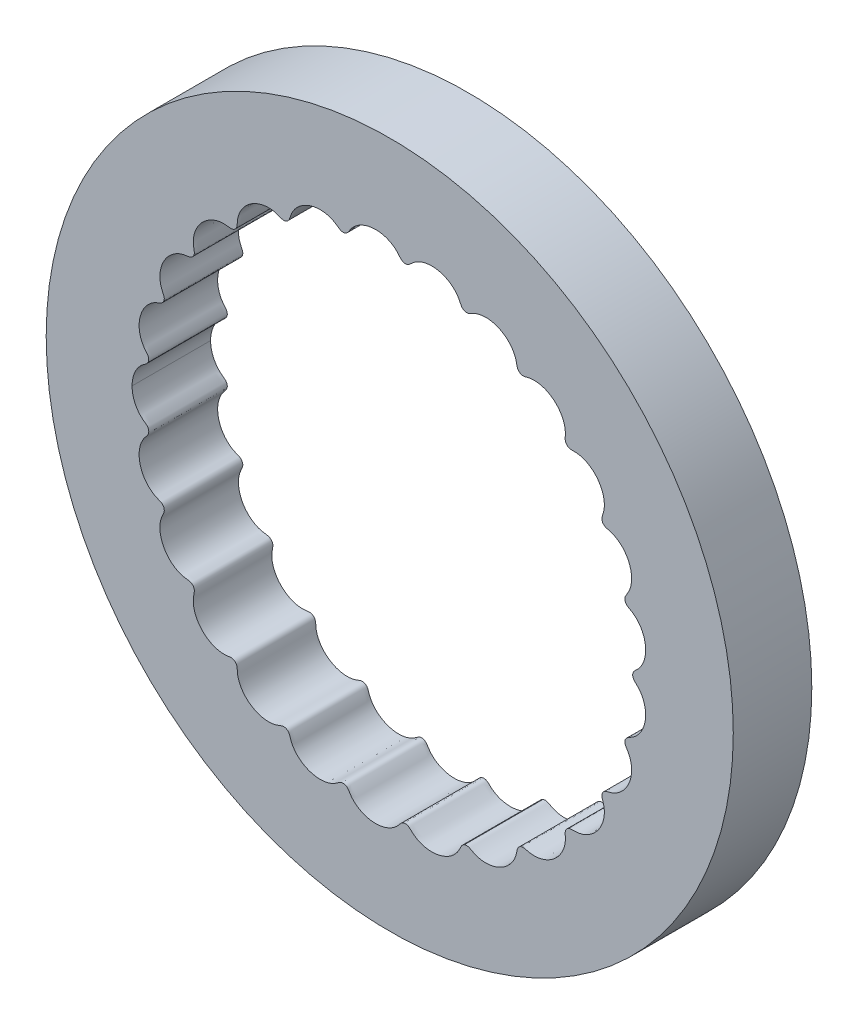
SolidWorks part; units mm, degrees
ref_plane "Plan de face" through (0, 0, 0) normal (0, 0, 1) x (1, 0, 0)
ref_plane "Plan de dessus" through (0, 0, 0) normal (0, 1, 0) x (1, 0, 0)
ref_plane "Plan de droite" through (0, 0, 0) normal (1, 0, 0) x (0, 0, -1)
sketch "Esquisse1" plane through (0, 0, 0) normal (0, 0, 1) x (1, 0, 0)
  line L0 (-1000, 0) -> (49000, 0) construction
  circle A1 centre (0, 0) radius 35
  spline S0 degree 4 poles (24.1426, 6.7991) (24.1177, 6.7609) (24.0692, 6.6836) (24.0004, 6.5645) (23.9483, 6.387) (23.9505, 6.1855) (24.0272, 5.9803) (24.1778, 5.8151) (24.3705, 5.7045) (24.5983, 5.5844) (24.8479, 5.4264) (25.1139, 5.2067) (25.3819, 4.9129) (25.6102, 4.583) (25.7961, 4.2235) (25.9371, 3.8403) (26.0305, 3.4429) (26.0756, 3.0373) (26.0716, 2.6291) (26.0179, 2.2244) (25.9151, 1.834) (25.7643, 1.4641) (25.5917, 1.1641) (25.4167, 0.9296) (25.2526, 0.7496) (25.1124, 0.6144) (24.9828, 0.4987) (24.8797, 0.3844) (24.8179, 0.2829) (24.7848, 0.2051) (24.7673, 0.1461) (24.7588, 0.1043) (24.7529, 0.0597) (24.7496, 0.0145) (24.7496, -0.0147) (24.7529, -0.06) (24.7589, -0.1048) (24.7675, -0.1468) (24.7852, -0.2061) (24.8185, -0.2842) (24.8808, -0.3859) (24.9847, -0.5005) (25.1148, -0.6166) (25.2554, -0.7525) (25.4198, -0.9333) (25.595, -1.1691) (25.7689, -1.4729) (25.9207, -1.8497) (26.0235, -2.2499) (26.0747, -2.6669) (26.0733, -3.0863) (26.0204, -3.5015) (25.917, -3.9063) (25.7644, -4.2943) (25.5662, -4.6548) (25.3259, -4.9815) (25.0816, -5.2331) (24.8519, -5.4186) (24.6671, -5.5402) (24.5395, -5.6139) (24.4102, -5.6846) (24.274, -5.758) (24.12, -5.8678) (23.9899, -6.0503) (23.9364, -6.2751) (23.9692, -6.4958) (24.0654, -6.6843) (24.1784, -6.8519) (24.2801, -7.019) (24.3936, -7.2353) (24.5034, -7.5077) (24.5951, -7.8454) (24.647, -8.2482) (24.6457, -8.6612) (24.576, -9.1855) (24.4176, -9.6961) (24.1747, -10.1766) (23.852, -10.6101) (23.5588, -10.9098) (23.241, -11.1578) (22.9466, -11.3291) (22.6921, -11.4408) (22.4727, -11.5135) (22.2939, -11.5615) (22.1013, -11.606) (21.9021, -11.6816) (21.7285, -11.8281) (21.6209, -12.0388) (21.6016, -12.2637) (21.6505, -12.4693) (21.7183, -12.6598) (21.7746, -12.8471) (21.8297, -13.085) (21.8672, -13.3762) (21.8707, -13.726) (21.8195, -14.1287) (21.7142, -14.528) (21.5148, -15.0178) (21.2331, -15.4721) (20.8771, -15.876) (20.4557, -16.2144) (20.0964, -16.4307) (19.7262, -16.5906) (19.3981, -16.6821) (19.1236, -16.7259) (18.8929, -16.7409) (18.7078, -16.7424) (18.5101, -16.7378) (18.2984, -16.7644) (18.0955, -16.8669) (17.9421, -17.0472) (17.8714, -17.2614) (17.8702, -17.4725) (17.8883, -17.6738) (17.8957, -17.8692) (17.8889, -18.1133) (17.8517, -18.4044) (17.7668, -18.7438) (17.6158, -19.1205) (17.4134, -19.4803) (17.1623, -19.8168) (16.8685, -20.1221) (16.5358, -20.3908) (16.1684, -20.6173) (15.771, -20.7957) (15.3688, -20.9145) (14.9702, -20.976) (14.6296, -20.9817) (14.3529, -20.9549) (14.1259, -20.9112) (13.9464, -20.866) (13.7558, -20.8128) (13.5435, -20.7889) (13.3222, -20.8417) (13.1314, -20.9817) (13.013, -21.1736) (12.9618, -21.3782) (12.9291, -21.5776) (12.887, -21.7685) (12.8188, -22.0029) (12.7093, -22.2752) (12.5416, -22.5821) (12.3006, -22.9086) (12.0142, -23.2057) (11.6866, -23.4682) (11.3255, -23.6897) (10.9359, -23.8661) (10.5233, -23.9928) (10.0937, -24.0655) (9.6744, -24.0792) (9.2731, -24.0382) (8.942, -23.9578) (8.6811, -23.862) (8.4724, -23.7624) (8.31, -23.6735) (8.1383, -23.575) (7.9372, -23.5018) (7.7049, -23.5021) (7.4781, -23.6007) (7.3169, -23.7729) (7.2208, -23.9706) (7.1156, -24.2034) (6.9743, -24.4604) (6.773, -24.7375) (6.4979, -25.0224) (6.1834, -25.2709) (5.8357, -25.4797) (5.4603, -25.6452) (5.0615, -25.7656) (4.6447, -25.8371) (4.2157, -25.8559) (3.7816, -25.8181) (3.3723, -25.7258) (2.9942, -25.5849) (2.6941, -25.4236) (2.4656, -25.2649) (2.2891, -25.1158) (2.1537, -24.9891) (2.0123, -24.8511) (1.8324, -24.7331) (1.553, -24.6659) (1.2621, -24.7546) (1.0754, -24.9576) (0.8891, -25.1941) (0.6967, -25.4018) (0.4476, -25.6153) (0.1257, -25.8218) (-0.2246, -25.9871) (-0.599, -26.1091) (-0.9909, -26.1853) (-1.3919, -26.2146) (-1.7962, -26.1958) (-2.1981, -26.1285) (-2.5915, -26.0119) (-2.9628, -25.849) (-3.3062, -25.6424) (-3.6154, -25.3948) (-3.8503, -25.1456) (-4.0231, -24.9087) (-4.157, -24.6911) (-4.2763, -24.5066) (-4.4563, -24.3545) (-4.6931, -24.2829) (-4.9238, -24.3097) (-5.115, -24.4061) (-5.2732, -24.5252) (-5.423, -24.6339) (-5.6174, -24.7592) (-5.864, -24.8876) (-6.1822, -25.0094) (-6.5751, -25.1011) (-6.9928, -25.1407) (-7.4281, -25.1231) (-7.8512, -25.0501) (-8.2556, -24.9263) (-8.636, -24.7563) (-8.9874, -24.5444) (-9.3058, -24.2932) (-9.5861, -24.0067) (-9.8229, -23.6892) (-9.9872, -23.3887) (-10.0948, -23.1158) (-10.1696, -22.8715) (-10.2411, -22.6635) (-10.3812, -22.4737) (-10.595, -22.3493) (-10.8256, -22.322) (-11.0338, -22.3709) (-11.2164, -22.4474) (-11.3887, -22.5149) (-11.6084, -22.5872) (-11.8793, -22.649) (-12.2179, -22.6866) (-12.6212, -22.6763) (-13.0353, -22.6095) (-13.4521, -22.4829) (-13.8453, -22.3049) (-14.2094, -22.0805) (-14.5395, -21.815) (-14.8313, -21.5131) (-15.0777, -21.1819) (-15.2753, -20.8275) (-15.4026, -20.5017) (-15.4765, -20.2177) (-15.5143, -19.9765) (-15.5318, -19.7817) (-15.5392, -19.5798) (-15.5656, -19.3704) (-15.6608, -19.166) (-15.8341, -19.0047) (-16.0476, -18.9266) (-16.2611, -18.9252) (-16.4568, -18.9543) (-16.6405, -18.9763) (-16.8713, -18.9908) (-17.1491, -18.9822) (-17.4862, -18.9332) (-17.8737, -18.8216) (-18.2576, -18.6527) (-18.6291, -18.4253) (-18.9648, -18.1541) (-19.2607, -17.8454) (-19.5135, -17.5053) (-19.7199, -17.1396) (-19.875, -16.7569) (-19.9769, -16.364) (-20.018, -16.0166) (-20.0178, -15.7231) (-19.9934, -15.4801) (-19.9613, -15.2872) (-19.9181, -15.0898) (-19.894, -14.8799) (-19.9394, -14.6589) (-20.0707, -14.462) (-20.2602, -14.3367) (-20.4672, -14.2852) (-20.6639, -14.2651) (-20.8473, -14.2402) (-21.0742, -14.196) (-21.3408, -14.1175) (-21.6546, -13.985) (-22.0015, -13.7794) (-22.3304, -13.5193) (-22.7055, -13.1302) (-23.0074, -12.6844) (-23.2291, -12.1981) (-23.3648, -11.6869) (-23.4186, -11.2774) (-23.4182, -10.8714) (-23.3703, -10.5248) (-23.296, -10.2407) (-23.211, -10.0117) (-23.1314, -9.8331) (-23.0402, -9.6526) (-22.9672, -9.4541) (-22.9601, -9.2287) (-23.0424, -9.0072) (-23.1982, -8.8407) (-23.3889, -8.7414) (-23.5777, -8.6723) (-23.7531, -8.5999) (-23.9662, -8.4963) (-24.2093, -8.3477) (-24.4803, -8.1356) (-24.7613, -7.8463) (-25.0085, -7.5133) (-25.2666, -7.049) (-25.4429, -6.5476) (-25.5339, -6.0256) (-25.5366, -5.4989) (-25.4855, -5.0889) (-25.3828, -4.696) (-25.2489, -4.3726) (-25.1052, -4.1164) (-24.9652, -3.9162) (-24.8431, -3.7634) (-24.7098, -3.6112) (-24.5919, -3.4354) (-24.5338, -3.2206) (-24.5604, -2.9926) (-24.6667, -2.797) (-24.8227, -2.6537) (-24.9897, -2.5393) (-25.1463, -2.4221) (-25.3325, -2.2638) (-25.5023, -2.0873) (-25.6545, -1.8958) (-25.7905, -1.6883) (-25.89, -1.512) (-25.979, -1.3255) (-26.0566, -1.1315) (-26.1214, -0.9307) (-26.1732, -0.7298) (-26.2073, -0.5457) (-26.2284, -0.3959) (-26.2405, -0.2557) (-26.247, -0.1691) (-26.2503, -0.0328) (-26.2503, 0.0323) (-26.2471, 0.1679) (-26.2407, 0.2542) (-26.2286, 0.3933) (-26.2078, 0.5423) (-26.1742, 0.7251) (-26.123, 0.925) (-26.0591, 1.1245) (-25.9824, 1.3176) (-25.8737, 1.547) (-25.7224, 1.8046) (-25.5451, 2.0414) (-25.3437, 2.2529) (-25.1596, 2.4115) (-25.0044, 2.5289) (-24.8386, 2.6423) (-24.6804, 2.7808) (-24.5546, 2.9935) (-24.5303, 3.2355) (-24.6, 3.4498) (-24.7118, 3.6094) (-24.804, 3.7191) (-24.9086, 3.8447) (-25.0204, 3.9911) (-25.1376, 4.1713) (-25.2521, 4.3886) (-25.3469, 4.6153) (-25.4409, 4.9075) (-25.515, 5.269) (-25.5464, 5.6988) (-25.509, 6.1899) (-25.401, 6.6704) (-25.2688, 7.0153) (-25.1588, 7.235) (-25.0985, 7.3418) knots 0 0 0 0 0 0.001685 0.003369 0.005054 0.006738 0.009006 0.011274 0.013086 0.014899 0.018524 0.022149 0.025774 0.029532 0.03329 0.037047 0.040805 0.044562 0.048319 0.052076 0.055834 0.059425 0.063017 0.064813 0.066609 0.068405 0.070201 0.071231 0.072261 0.072776 0.073291 0.073548 0.073806 0.074321 0.074838 0.075097 0.075356 0.075873 0.07639 0.077425 0.07846 0.080263 0.082066 0.083868 0.085671 0.089277 0.092883 0.09675 0.100617 0.104484 0.108351 0.112188 0.116026 0.119864 0.123701 0.127327 0.130952 0.132764 0.134577 0.135483 0.13639 0.138202 0.140296 0.142389 0.144459 0.146528 0.148331 0.150133 0.151935 0.153737 0.157342 0.160946 0.164812 0.168678 0.172544 0.180416 0.184421 0.188427 0.192432 0.195844 0.199256 0.200962 0.202668 0.204374 0.20608 0.208269 0.210458 0.212527 0.214596 0.216398 0.2182 0.220001 0.221803 0.225407 0.22901 0.232875 0.23674 0.240605 0.248477 0.252483 0.256489 0.260496 0.263908 0.26732 0.269026 0.270732 0.272438 0.274144 0.276335 0.278527 0.280595 0.282663 0.284464 0.286266 0.288067 0.289868 0.293471 0.297074 0.300938 0.304802 0.308666 0.31253 0.316537 0.320545 0.324552 0.328559 0.331971 0.335384 0.33709 0.338796 0.340502 0.342208 0.344401 0.346595 0.348662 0.350729 0.35253 0.354331 0.356132 0.357933 0.361536 0.365138 0.369001 0.372864 0.376727 0.38059 0.384598 0.388606 0.392614 0.396623 0.400035 0.403448 0.405154 0.40686 0.408567 0.410273 0.412468 0.414663 0.416905 0.419148 0.420948 0.422747 0.426346 0.429946 0.433545 0.437321 0.441097 0.444873 0.44865 0.452659 0.456668 0.460677 0.464686 0.468099 0.471512 0.473218 0.474925 0.476631 0.478338 0.480534 0.48273 0.48702 0.488749 0.490478 0.493937 0.497395 0.500854 0.50453 0.508207 0.511883 0.515559 0.519335 0.523111 0.526887 0.530662 0.534262 0.537861 0.54146 0.543259 0.545059 0.547301 0.549542 0.551738 0.553933 0.55564 0.557346 0.559053 0.560759 0.564172 0.567585 0.571593 0.575602 0.57961 0.583619 0.587396 0.591172 0.594949 0.598726 0.602325 0.605924 0.609523 0.611323 0.613123 0.615366 0.61761 0.619804 0.621998 0.623704 0.625411 0.627117 0.628823 0.632235 0.635648 0.639656 0.643663 0.647671 0.651679 0.655542 0.659406 0.663269 0.667133 0.670735 0.674338 0.676139 0.67794 0.679742 0.681543 0.68361 0.685678 0.68787 0.690063 0.691769 0.693475 0.695181 0.696887 0.700299 0.703711 0.707718 0.711725 0.715732 0.719739 0.723603 0.727468 0.731332 0.735197 0.7388 0.742403 0.744204 0.746006 0.747808 0.749609 0.751678 0.753746 0.755937 0.758127 0.759833 0.761539 0.763245 0.764951 0.768363 0.771775 0.775781 0.779787 0.783793 0.791664 0.795529 0.799395 0.80326 0.806864 0.810468 0.81227 0.814073 0.815875 0.817677 0.819746 0.821815 0.823999 0.826183 0.827931 0.82968 0.831429 0.833177 0.836675 0.840172 0.844094 0.848015 0.851937 0.859725 0.863591 0.867458 0.871324 0.874929 0.878534 0.880337 0.882139 0.883942 0.885745 0.887814 0.889884 0.891953 0.894023 0.895826 0.897629 0.899432 0.901235 0.904841 0.906644 0.908448 0.910381 0.912315 0.914249 0.916183 0.918117 0.92005 0.921017 0.921984 0.922951 0.923918 0.924879 0.925839 0.9268 0.927761 0.929682 0.931604 0.933525 0.935447 0.937368 0.93929 0.942875 0.94646 0.948253 0.950045 0.951838 0.95363 0.955683 0.957735 0.960756 0.962266 0.963777 0.964909 0.96604 0.968304 0.970568 0.972832 0.975095 0.977359 0.981887 0.986415 0.990943 0.995472 1 1 1 1 1 construction
  spline S1 degree 4 poles (24.75, 0) (24.75, -0.0119) (24.7507, -0.0298) (24.7529, -0.06) (24.7589, -0.1048) (24.7675, -0.1468) (24.7852, -0.2061) (24.8185, -0.2842) (24.8808, -0.3859) (24.9847, -0.5005) (25.1148, -0.6166) (25.2554, -0.7525) (25.4198, -0.9333) (25.595, -1.1691) (25.7689, -1.4729) (25.9207, -1.8497) (26.0235, -2.2499) (26.0747, -2.6669) (26.0733, -3.0863) (26.0204, -3.5015) (25.917, -3.9063) (25.7644, -4.2943) (25.5662, -4.6548) (25.3259, -4.9815) (25.0816, -5.2331) (24.8519, -5.4186) (24.6671, -5.5402) (24.5395, -5.6139) (24.4102, -5.6846) (24.274, -5.758) (24.12, -5.8678) (23.9899, -6.0503) (23.9364, -6.2751) (23.9692, -6.4958) (24.0654, -6.6843) (24.1784, -6.8519) (24.2801, -7.019) (24.3936, -7.2353) (24.5034, -7.5077) (24.5951, -7.8454) (24.647, -8.2482) (24.6457, -8.6612) (24.576, -9.1855) (24.4176, -9.6961) (24.1747, -10.1766) (23.852, -10.6101) (23.5588, -10.9098) (23.241, -11.1578) (22.9466, -11.3291) (22.6921, -11.4408) (22.4727, -11.5135) (22.2939, -11.5615) (22.1013, -11.606) (21.9021, -11.6816) (21.7285, -11.8281) (21.6209, -12.0388) (21.6016, -12.2637) (21.6505, -12.4693) (21.7183, -12.6598) (21.7746, -12.8471) (21.8297, -13.085) (21.8672, -13.3762) (21.8707, -13.726) (21.8195, -14.1287) (21.7142, -14.528) (21.5148, -15.0178) (21.2331, -15.4721) (20.8771, -15.876) (20.4557, -16.2144) (20.0964, -16.4307) (19.7262, -16.5906) (19.3981, -16.6821) (19.1236, -16.7259) (18.8929, -16.7409) (18.7078, -16.7424) (18.5101, -16.7378) (18.2984, -16.7644) (18.0955, -16.8669) (17.9421, -17.0472) (17.8714, -17.2614) (17.8702, -17.4725) (17.8883, -17.6738) (17.8957, -17.8692) (17.8889, -18.1133) (17.8517, -18.4044) (17.7668, -18.7438) (17.6158, -19.1205) (17.4134, -19.4803) (17.1623, -19.8168) (16.8685, -20.1221) (16.5358, -20.3908) (16.1684, -20.6173) (15.771, -20.7957) (15.3688, -20.9145) (14.9702, -20.976) (14.6296, -20.9817) (14.3529, -20.9549) (14.1259, -20.9112) (13.9464, -20.866) (13.7558, -20.8128) (13.5435, -20.7889) (13.3222, -20.8417) (13.1314, -20.9817) (13.013, -21.1736) (12.9618, -21.3782) (12.9291, -21.5776) (12.887, -21.7685) (12.8188, -22.0029) (12.7093, -22.2752) (12.5416, -22.5821) (12.3006, -22.9086) (12.0142, -23.2057) (11.6866, -23.4682) (11.3255, -23.6897) (10.9359, -23.8661) (10.5233, -23.9928) (10.0937, -24.0655) (9.6744, -24.0792) (9.2731, -24.0382) (8.942, -23.9578) (8.6811, -23.862) (8.4724, -23.7624) (8.31, -23.6735) (8.1383, -23.575) (7.9372, -23.5018) (7.7049, -23.5021) (7.4781, -23.6007) (7.3169, -23.7729) (7.2208, -23.9706) (7.1156, -24.2034) (6.9743, -24.4604) (6.773, -24.7375) (6.4979, -25.0224) (6.1834, -25.2709) (5.8357, -25.4797) (5.4603, -25.6452) (5.0615, -25.7656) (4.6447, -25.8371) (4.2157, -25.8559) (3.7816, -25.8181) (3.3723, -25.7258) (2.9942, -25.5849) (2.6941, -25.4236) (2.4656, -25.2649) (2.2891, -25.1158) (2.1537, -24.9891) (2.0123, -24.8511) (1.8324, -24.7331) (1.553, -24.6659) (1.2621, -24.7546) (1.0754, -24.9576) (0.8891, -25.1941) (0.6967, -25.4018) (0.4476, -25.6153) (0.1257, -25.8218) (-0.2246, -25.9871) (-0.599, -26.1091) (-0.9909, -26.1853) (-1.3919, -26.2146) (-1.7962, -26.1958) (-2.1981, -26.1285) (-2.5915, -26.0119) (-2.9628, -25.849) (-3.3062, -25.6424) (-3.6154, -25.3948) (-3.8503, -25.1456) (-4.0231, -24.9087) (-4.157, -24.6911) (-4.2763, -24.5066) (-4.4563, -24.3545) (-4.6931, -24.2829) (-4.9238, -24.3097) (-5.115, -24.4061) (-5.2732, -24.5252) (-5.423, -24.6339) (-5.6174, -24.7592) (-5.864, -24.8876) (-6.1822, -25.0094) (-6.5751, -25.1011) (-6.9928, -25.1407) (-7.4281, -25.1231) (-7.8512, -25.0501) (-8.2556, -24.9263) (-8.636, -24.7563) (-8.9874, -24.5444) (-9.3058, -24.2932) (-9.5861, -24.0067) (-9.8229, -23.6892) (-9.9872, -23.3887) (-10.0948, -23.1158) (-10.1696, -22.8715) (-10.2411, -22.6635) (-10.3812, -22.4737) (-10.595, -22.3493) (-10.8256, -22.322) (-11.0338, -22.3709) (-11.2164, -22.4474) (-11.3887, -22.5149) (-11.6084, -22.5872) (-11.8793, -22.649) (-12.2179, -22.6866) (-12.6212, -22.6763) (-13.0353, -22.6095) (-13.4521, -22.4829) (-13.8453, -22.3049) (-14.2094, -22.0805) (-14.5395, -21.815) (-14.8313, -21.5131) (-15.0777, -21.1819) (-15.2753, -20.8275) (-15.4026, -20.5017) (-15.4765, -20.2177) (-15.5143, -19.9765) (-15.5318, -19.7817) (-15.5392, -19.5798) (-15.5656, -19.3704) (-15.6608, -19.166) (-15.8341, -19.0047) (-16.0476, -18.9266) (-16.2611, -18.9252) (-16.4568, -18.9543) (-16.6405, -18.9763) (-16.8713, -18.9908) (-17.1491, -18.9822) (-17.4862, -18.9332) (-17.8737, -18.8216) (-18.2576, -18.6527) (-18.6291, -18.4253) (-18.9648, -18.1541) (-19.2607, -17.8454) (-19.5135, -17.5053) (-19.7199, -17.1396) (-19.875, -16.7569) (-19.9769, -16.364) (-20.018, -16.0166) (-20.0178, -15.7231) (-19.9934, -15.4801) (-19.9613, -15.2872) (-19.9181, -15.0898) (-19.894, -14.8799) (-19.9394, -14.6589) (-20.0707, -14.462) (-20.2602, -14.3367) (-20.4672, -14.2852) (-20.6639, -14.2651) (-20.8473, -14.2402) (-21.0742, -14.196) (-21.3408, -14.1175) (-21.6546, -13.985) (-22.0015, -13.7794) (-22.3304, -13.5193) (-22.7055, -13.1302) (-23.0074, -12.6844) (-23.2291, -12.1981) (-23.3648, -11.6869) (-23.4186, -11.2774) (-23.4182, -10.8714) (-23.3703, -10.5248) (-23.296, -10.2407) (-23.211, -10.0117) (-23.1314, -9.8331) (-23.0402, -9.6526) (-22.9672, -9.4541) (-22.9601, -9.2287) (-23.0424, -9.0072) (-23.1982, -8.8407) (-23.3889, -8.7414) (-23.5777, -8.6723) (-23.7531, -8.5999) (-23.9662, -8.4963) (-24.2093, -8.3477) (-24.4803, -8.1356) (-24.7613, -7.8463) (-25.0085, -7.5133) (-25.2666, -7.049) (-25.4429, -6.5476) (-25.5339, -6.0256) (-25.5366, -5.4989) (-25.4855, -5.0889) (-25.3828, -4.696) (-25.2489, -4.3726) (-25.1052, -4.1164) (-24.9652, -3.9162) (-24.8431, -3.7634) (-24.7098, -3.6112) (-24.5919, -3.4354) (-24.5338, -3.2206) (-24.5604, -2.9926) (-24.6667, -2.797) (-24.8227, -2.6537) (-24.9897, -2.5393) (-25.1463, -2.4221) (-25.3325, -2.2638) (-25.5023, -2.0873) (-25.6545, -1.8958) (-25.7905, -1.6883) (-25.89, -1.512) (-25.979, -1.3255) (-26.0566, -1.1315) (-26.1214, -0.9307) (-26.1732, -0.7298) (-26.2073, -0.5457) (-26.2284, -0.3959) (-26.2405, -0.2557) (-26.247, -0.1691) (-26.2495, -0.0667) (-26.25, -0.0223) (-26.25, 0) knots 0.074321 0.074321 0.074321 0.074321 0.074321 0.074838 0.075097 0.075356 0.075873 0.07639 0.077425 0.07846 0.080263 0.082066 0.083868 0.085671 0.089277 0.092883 0.09675 0.100617 0.104484 0.108351 0.112188 0.116026 0.119864 0.123701 0.127327 0.130952 0.132764 0.134577 0.135483 0.13639 0.138202 0.140296 0.142389 0.144459 0.146528 0.148331 0.150133 0.151935 0.153737 0.157342 0.160946 0.164812 0.168678 0.172544 0.180416 0.184421 0.188427 0.192432 0.195844 0.199256 0.200962 0.202668 0.204374 0.20608 0.208269 0.210458 0.212527 0.214596 0.216398 0.2182 0.220001 0.221803 0.225407 0.22901 0.232875 0.23674 0.240605 0.248477 0.252483 0.256489 0.260496 0.263908 0.26732 0.269026 0.270732 0.272438 0.274144 0.276335 0.278527 0.280595 0.282663 0.284464 0.286266 0.288067 0.289868 0.293471 0.297074 0.300938 0.304802 0.308666 0.31253 0.316537 0.320545 0.324552 0.328559 0.331971 0.335384 0.33709 0.338796 0.340502 0.342208 0.344401 0.346595 0.348662 0.350729 0.35253 0.354331 0.356132 0.357933 0.361536 0.365138 0.369001 0.372864 0.376727 0.38059 0.384598 0.388606 0.392614 0.396623 0.400035 0.403448 0.405154 0.40686 0.408567 0.410273 0.412468 0.414663 0.416905 0.419148 0.420948 0.422747 0.426346 0.429946 0.433545 0.437321 0.441097 0.444873 0.44865 0.452659 0.456668 0.460677 0.464686 0.468099 0.471512 0.473218 0.474925 0.476631 0.478338 0.480534 0.48273 0.48702 0.488749 0.490478 0.493937 0.497395 0.500854 0.50453 0.508207 0.511883 0.515559 0.519335 0.523111 0.526887 0.530662 0.534262 0.537861 0.54146 0.543259 0.545059 0.547301 0.549542 0.551738 0.553933 0.55564 0.557346 0.559053 0.560759 0.564172 0.567585 0.571593 0.575602 0.57961 0.583619 0.587396 0.591172 0.594949 0.598726 0.602325 0.605924 0.609523 0.611323 0.613123 0.615366 0.61761 0.619804 0.621998 0.623704 0.625411 0.627117 0.628823 0.632235 0.635648 0.639656 0.643663 0.647671 0.651679 0.655542 0.659406 0.663269 0.667133 0.670735 0.674338 0.676139 0.67794 0.679742 0.681543 0.68361 0.685678 0.68787 0.690063 0.691769 0.693475 0.695181 0.696887 0.700299 0.703711 0.707718 0.711725 0.715732 0.719739 0.723603 0.727468 0.731332 0.735197 0.7388 0.742403 0.744204 0.746006 0.747808 0.749609 0.751678 0.753746 0.755937 0.758127 0.759833 0.761539 0.763245 0.764951 0.768363 0.771775 0.775781 0.779787 0.783793 0.791664 0.795529 0.799395 0.80326 0.806864 0.810468 0.81227 0.814073 0.815875 0.817677 0.819746 0.821815 0.823999 0.826183 0.827931 0.82968 0.831429 0.833177 0.836675 0.840172 0.844094 0.848015 0.851937 0.859725 0.863591 0.867458 0.871324 0.874929 0.878534 0.880337 0.882139 0.883942 0.885745 0.887814 0.889884 0.891953 0.894023 0.895826 0.897629 0.899432 0.901235 0.904841 0.906644 0.908448 0.910381 0.912315 0.914249 0.916183 0.918117 0.92005 0.921017 0.921984 0.922951 0.923918 0.923918 0.923918 0.923918 0.923918
  spline S2 degree 4 poles (24.75, 0) (24.75, 0.0119) (24.7507, 0.0298) (24.7529, 0.06) (24.7589, 0.1048) (24.7675, 0.1468) (24.7852, 0.2061) (24.8185, 0.2842) (24.8808, 0.3859) (24.9847, 0.5005) (25.1148, 0.6166) (25.2554, 0.7525) (25.4198, 0.9333) (25.595, 1.1691) (25.7689, 1.4729) (25.9207, 1.8497) (26.0235, 2.2499) (26.0747, 2.6669) (26.0733, 3.0863) (26.0204, 3.5015) (25.917, 3.9063) (25.7644, 4.2943) (25.5662, 4.6548) (25.3259, 4.9815) (25.0816, 5.2331) (24.8519, 5.4186) (24.6671, 5.5402) (24.5395, 5.6139) (24.4102, 5.6846) (24.274, 5.758) (24.12, 5.8678) (23.9899, 6.0503) (23.9364, 6.2751) (23.9692, 6.4958) (24.0654, 6.6843) (24.1784, 6.8519) (24.2801, 7.019) (24.3936, 7.2353) (24.5034, 7.5077) (24.5951, 7.8454) (24.647, 8.2482) (24.6457, 8.6612) (24.576, 9.1855) (24.4176, 9.6961) (24.1747, 10.1766) (23.852, 10.6101) (23.5588, 10.9098) (23.241, 11.1578) (22.9466, 11.3291) (22.6921, 11.4408) (22.4727, 11.5135) (22.2939, 11.5615) (22.1013, 11.606) (21.9021, 11.6816) (21.7285, 11.8281) (21.6209, 12.0388) (21.6016, 12.2637) (21.6505, 12.4693) (21.7183, 12.6598) (21.7746, 12.8471) (21.8297, 13.085) (21.8672, 13.3762) (21.8707, 13.726) (21.8195, 14.1287) (21.7142, 14.528) (21.5148, 15.0178) (21.2331, 15.4721) (20.8771, 15.876) (20.4557, 16.2144) (20.0964, 16.4307) (19.7262, 16.5906) (19.3981, 16.6821) (19.1236, 16.7259) (18.8929, 16.7409) (18.7078, 16.7424) (18.5101, 16.7378) (18.2984, 16.7644) (18.0955, 16.8669) (17.9421, 17.0472) (17.8714, 17.2614) (17.8702, 17.4725) (17.8883, 17.6738) (17.8957, 17.8692) (17.8889, 18.1133) (17.8517, 18.4044) (17.7668, 18.7438) (17.6158, 19.1205) (17.4134, 19.4803) (17.1623, 19.8168) (16.8685, 20.1221) (16.5358, 20.3908) (16.1684, 20.6173) (15.771, 20.7957) (15.3688, 20.9145) (14.9702, 20.976) (14.6296, 20.9817) (14.3529, 20.9549) (14.1259, 20.9112) (13.9464, 20.866) (13.7558, 20.8128) (13.5435, 20.7889) (13.3222, 20.8417) (13.1314, 20.9817) (13.013, 21.1736) (12.9618, 21.3782) (12.9291, 21.5776) (12.887, 21.7685) (12.8188, 22.0029) (12.7093, 22.2752) (12.5416, 22.5821) (12.3006, 22.9086) (12.0142, 23.2057) (11.6866, 23.4682) (11.3255, 23.6897) (10.9359, 23.8661) (10.5233, 23.9928) (10.0937, 24.0655) (9.6744, 24.0792) (9.2731, 24.0382) (8.942, 23.9578) (8.6811, 23.862) (8.4724, 23.7624) (8.31, 23.6735) (8.1383, 23.575) (7.9372, 23.5018) (7.7049, 23.5021) (7.4781, 23.6007) (7.3169, 23.7729) (7.2208, 23.9706) (7.1156, 24.2034) (6.9743, 24.4604) (6.773, 24.7375) (6.4979, 25.0224) (6.1834, 25.2709) (5.8357, 25.4797) (5.4603, 25.6452) (5.0615, 25.7656) (4.6447, 25.8371) (4.2157, 25.8559) (3.7816, 25.8181) (3.3723, 25.7258) (2.9942, 25.5849) (2.6941, 25.4236) (2.4656, 25.2649) (2.2891, 25.1158) (2.1537, 24.9891) (2.0123, 24.8511) (1.8324, 24.7331) (1.553, 24.6659) (1.2621, 24.7546) (1.0754, 24.9576) (0.8891, 25.1941) (0.6967, 25.4018) (0.4476, 25.6153) (0.1257, 25.8218) (-0.2246, 25.9871) (-0.599, 26.1091) (-0.9909, 26.1853) (-1.3919, 26.2146) (-1.7962, 26.1958) (-2.1981, 26.1285) (-2.5915, 26.0119) (-2.9628, 25.849) (-3.3062, 25.6424) (-3.6154, 25.3948) (-3.8503, 25.1456) (-4.0231, 24.9087) (-4.157, 24.6911) (-4.2763, 24.5066) (-4.4563, 24.3545) (-4.6931, 24.2829) (-4.9238, 24.3097) (-5.115, 24.4061) (-5.2732, 24.5252) (-5.423, 24.6339) (-5.6174, 24.7592) (-5.864, 24.8876) (-6.1822, 25.0094) (-6.5751, 25.1011) (-6.9928, 25.1407) (-7.4281, 25.1231) (-7.8512, 25.0501) (-8.2556, 24.9263) (-8.636, 24.7563) (-8.9874, 24.5444) (-9.3058, 24.2932) (-9.5861, 24.0067) (-9.8229, 23.6892) (-9.9872, 23.3887) (-10.0948, 23.1158) (-10.1696, 22.8715) (-10.2411, 22.6635) (-10.3812, 22.4737) (-10.595, 22.3493) (-10.8256, 22.322) (-11.0338, 22.3709) (-11.2164, 22.4474) (-11.3887, 22.5149) (-11.6084, 22.5872) (-11.8793, 22.649) (-12.2179, 22.6866) (-12.6212, 22.6763) (-13.0353, 22.6095) (-13.4521, 22.4829) (-13.8453, 22.3049) (-14.2094, 22.0805) (-14.5395, 21.815) (-14.8313, 21.5131) (-15.0777, 21.1819) (-15.2753, 20.8275) (-15.4026, 20.5017) (-15.4765, 20.2177) (-15.5143, 19.9765) (-15.5318, 19.7817) (-15.5392, 19.5798) (-15.5656, 19.3704) (-15.6608, 19.166) (-15.8341, 19.0047) (-16.0476, 18.9266) (-16.2611, 18.9252) (-16.4568, 18.9543) (-16.6405, 18.9763) (-16.8713, 18.9908) (-17.1491, 18.9822) (-17.4862, 18.9332) (-17.8737, 18.8216) (-18.2576, 18.6527) (-18.6291, 18.4253) (-18.9648, 18.1541) (-19.2607, 17.8454) (-19.5135, 17.5053) (-19.7199, 17.1396) (-19.875, 16.7569) (-19.9769, 16.364) (-20.018, 16.0166) (-20.0178, 15.7231) (-19.9934, 15.4801) (-19.9613, 15.2872) (-19.9181, 15.0898) (-19.894, 14.8799) (-19.9394, 14.6589) (-20.0707, 14.462) (-20.2602, 14.3367) (-20.4672, 14.2852) (-20.6639, 14.2651) (-20.8473, 14.2402) (-21.0742, 14.196) (-21.3408, 14.1175) (-21.6546, 13.985) (-22.0015, 13.7794) (-22.3304, 13.5193) (-22.7055, 13.1302) (-23.0074, 12.6844) (-23.2291, 12.1981) (-23.3648, 11.6869) (-23.4186, 11.2774) (-23.4182, 10.8714) (-23.3703, 10.5248) (-23.296, 10.2407) (-23.211, 10.0117) (-23.1314, 9.8331) (-23.0402, 9.6526) (-22.9672, 9.4541) (-22.9601, 9.2287) (-23.0424, 9.0072) (-23.1982, 8.8407) (-23.3889, 8.7414) (-23.5777, 8.6723) (-23.7531, 8.5999) (-23.9662, 8.4963) (-24.2093, 8.3477) (-24.4803, 8.1356) (-24.7613, 7.8463) (-25.0085, 7.5133) (-25.2666, 7.049) (-25.4429, 6.5476) (-25.5339, 6.0256) (-25.5366, 5.4989) (-25.4855, 5.0889) (-25.3828, 4.696) (-25.2489, 4.3726) (-25.1052, 4.1164) (-24.9652, 3.9162) (-24.8431, 3.7634) (-24.7098, 3.6112) (-24.5919, 3.4354) (-24.5338, 3.2206) (-24.5604, 2.9926) (-24.6667, 2.797) (-24.8227, 2.6537) (-24.9897, 2.5393) (-25.1463, 2.4221) (-25.3325, 2.2638) (-25.5023, 2.0873) (-25.6545, 1.8958) (-25.7905, 1.6883) (-25.89, 1.512) (-25.979, 1.3255) (-26.0566, 1.1315) (-26.1214, 0.9307) (-26.1732, 0.7298) (-26.2073, 0.5457) (-26.2284, 0.3959) (-26.2405, 0.2557) (-26.247, 0.1691) (-26.2495, 0.0667) (-26.25, 0.0223) (-26.25, 0) knots 0.074321 0.074321 0.074321 0.074321 0.074321 0.074838 0.075097 0.075356 0.075873 0.07639 0.077425 0.07846 0.080263 0.082066 0.083868 0.085671 0.089277 0.092883 0.09675 0.100617 0.104484 0.108351 0.112188 0.116026 0.119864 0.123701 0.127327 0.130952 0.132764 0.134577 0.135483 0.13639 0.138202 0.140296 0.142389 0.144459 0.146528 0.148331 0.150133 0.151935 0.153737 0.157342 0.160946 0.164812 0.168678 0.172544 0.180416 0.184421 0.188427 0.192432 0.195844 0.199256 0.200962 0.202668 0.204374 0.20608 0.208269 0.210458 0.212527 0.214596 0.216398 0.2182 0.220001 0.221803 0.225407 0.22901 0.232875 0.23674 0.240605 0.248477 0.252483 0.256489 0.260496 0.263908 0.26732 0.269026 0.270732 0.272438 0.274144 0.276335 0.278527 0.280595 0.282663 0.284464 0.286266 0.288067 0.289868 0.293471 0.297074 0.300938 0.304802 0.308666 0.31253 0.316537 0.320545 0.324552 0.328559 0.331971 0.335384 0.33709 0.338796 0.340502 0.342208 0.344401 0.346595 0.348662 0.350729 0.35253 0.354331 0.356132 0.357933 0.361536 0.365138 0.369001 0.372864 0.376727 0.38059 0.384598 0.388606 0.392614 0.396623 0.400035 0.403448 0.405154 0.40686 0.408567 0.410273 0.412468 0.414663 0.416905 0.419148 0.420948 0.422747 0.426346 0.429946 0.433545 0.437321 0.441097 0.444873 0.44865 0.452659 0.456668 0.460677 0.464686 0.468099 0.471512 0.473218 0.474925 0.476631 0.478338 0.480534 0.48273 0.48702 0.488749 0.490478 0.493937 0.497395 0.500854 0.50453 0.508207 0.511883 0.515559 0.519335 0.523111 0.526887 0.530662 0.534262 0.537861 0.54146 0.543259 0.545059 0.547301 0.549542 0.551738 0.553933 0.55564 0.557346 0.559053 0.560759 0.564172 0.567585 0.571593 0.575602 0.57961 0.583619 0.587396 0.591172 0.594949 0.598726 0.602325 0.605924 0.609523 0.611323 0.613123 0.615366 0.61761 0.619804 0.621998 0.623704 0.625411 0.627117 0.628823 0.632235 0.635648 0.639656 0.643663 0.647671 0.651679 0.655542 0.659406 0.663269 0.667133 0.670735 0.674338 0.676139 0.67794 0.679742 0.681543 0.68361 0.685678 0.68787 0.690063 0.691769 0.693475 0.695181 0.696887 0.700299 0.703711 0.707718 0.711725 0.715732 0.719739 0.723603 0.727468 0.731332 0.735197 0.7388 0.742403 0.744204 0.746006 0.747808 0.749609 0.751678 0.753746 0.755937 0.758127 0.759833 0.761539 0.763245 0.764951 0.768363 0.771775 0.775781 0.779787 0.783793 0.791664 0.795529 0.799395 0.80326 0.806864 0.810468 0.81227 0.814073 0.815875 0.817677 0.819746 0.821815 0.823999 0.826183 0.827931 0.82968 0.831429 0.833177 0.836675 0.840172 0.844094 0.848015 0.851937 0.859725 0.863591 0.867458 0.871324 0.874929 0.878534 0.880337 0.882139 0.883942 0.885745 0.887814 0.889884 0.891953 0.894023 0.895826 0.897629 0.899432 0.901235 0.904841 0.906644 0.908448 0.910381 0.912315 0.914249 0.916183 0.918117 0.92005 0.921017 0.921984 0.922951 0.923918 0.923918 0.923918 0.923918 0.923918
  dimension "D1" = 70
extrude "Boss.-Extru.1" add sketch "Esquisse1" along normal blind 8
equation "\"R\"= 26'Radius of the rotor"
equation "\"E\"= 0.75'Eccentricity from input shaft to center of rotor"
equation "\"Rr\"= 0.5'Roller radius"
equation "\"N\"= 26'Amount of rollers"
